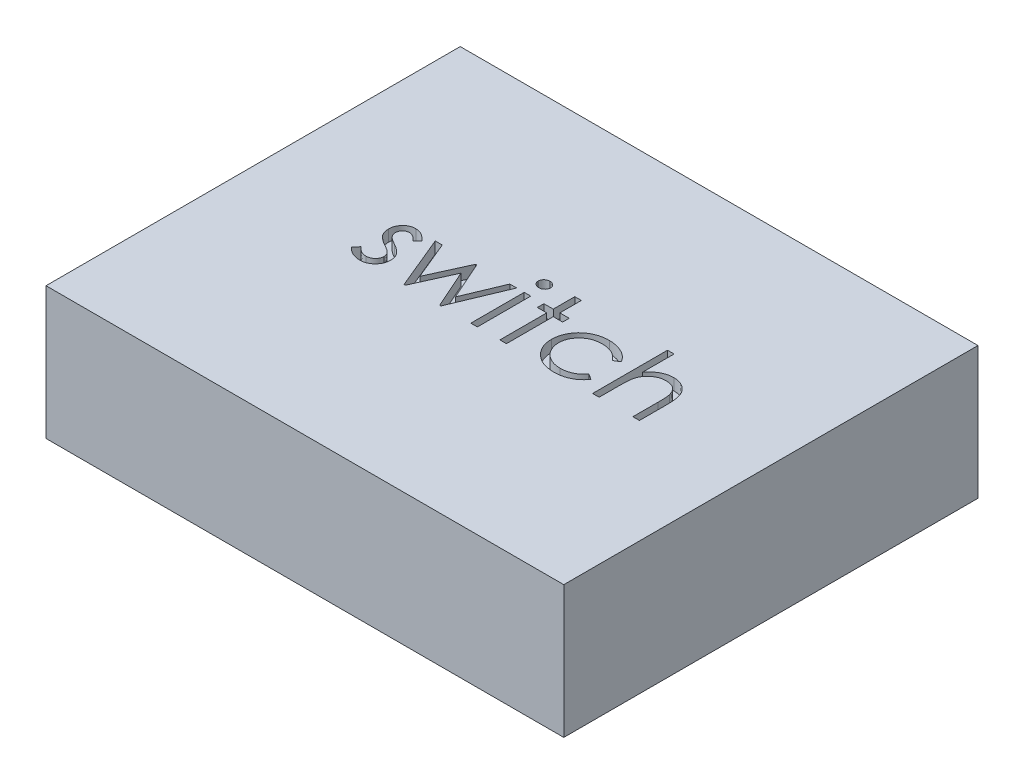
SolidWorks part; units mm, degrees
ref_plane "Front Plane" through (0, 0, 0) normal (0, 0, 1) x (1, 0, 0)
ref_plane "Top Plane" through (0, 0, 0) normal (0, 1, 0) x (1, 0, 0)
ref_plane "Right Plane" through (0, 0, 0) normal (1, 0, 0) x (0, 0, -1)
sketch "Szkic1" plane through (0, 0, 0) normal (0, 1, 0) x (1, 0, 0)
  line L0 (45, 36) -> (-45, -36) construction
  line L1 (-45, 36) -> (45, 36)
  line L2 (-45, 36) -> (-45, -36)
  line L3 (-45, -36) -> (45, -36)
  line L4 (45, 36) -> (45, -36)
  point P4 (48.5923, 21.1786)
  point P5 (45, 22.7592)
  dimension "D1" = 90
  dimension "D2" = 72
extrude "Dodanie-wyciągnięcie1" add sketch "Szkic1" along normal blind 23
sketch "Szkic2" plane through (0, 23, 0) normal (0, 1, 0) x (1, 0, 0)
  text T0 "switch" font "Century Gothic" height in points 48
extrude "Wytnij-wyciągnięcie1" cut sketch "Szkic2" against normal blind 2
